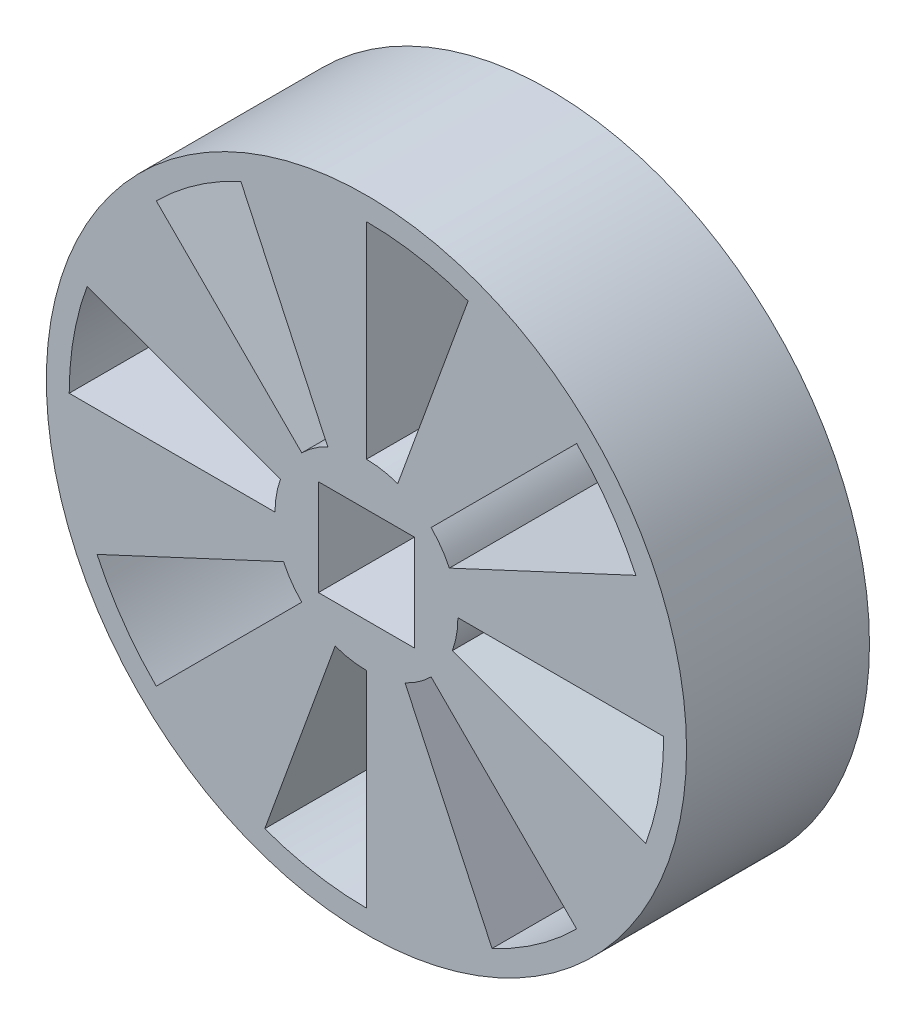
SolidWorks part; units mm, degrees
ref_plane "Спереди" through (0, 0, 0) normal (0, 0, 1) x (1, 0, 0)
ref_plane "Сверху" through (0, 0, 0) normal (0, 1, 0) x (1, 0, 0)
ref_plane "Справа" through (0, 0, 0) normal (1, 0, 0) x (0, 0, -1)
sketch "Эскиз2" plane through (0, 0, 0) normal (0, 0, 1) x (1, 0, 0)
  line L0 (0, 10) -> (0, 32.5)
  line L1 (-5.25, -5.25) -> (5.25, -5.25)
  line L2 (-5.25, -5.25) -> (-5.25, 5.25)
  line L3 (-5.25, 5.25) -> (5.25, 5.25)
  line L4 (5.25, -5.25) -> (5.25, 5.25)
  line L5 (-5.25, -5.25) -> (5.25, 5.25) construction
  line L6 (-5.25, 5.25) -> (5.25, -5.25) construction
  line L7 (3.4202, 9.3969) -> (11.1157, 30.54)
  line L8 (7.0711, 7.0711) -> (22.981, 22.981)
  line L9 (9.0631, 4.2262) -> (29.455, 13.7351)
  line L10 (10, 0) -> (32.5, 0)
  line L11 (9.3969, -3.4202) -> (30.54, -11.1157)
  line L12 (7.0711, -7.0711) -> (22.981, -22.981)
  line L13 (4.2262, -9.0631) -> (13.7351, -29.455)
  line L14 (0, -10) -> (0, -32.5)
  line L15 (-3.4202, -9.3969) -> (-11.1157, -30.54)
  line L16 (-7.0711, -7.0711) -> (-22.981, -22.981)
  line L17 (-9.0631, -4.2262) -> (-29.455, -13.7351)
  line L18 (-10, 0) -> (-32.5, 0)
  line L19 (-9.3969, 3.4202) -> (-30.54, 11.1157)
  line L20 (-7.0711, 7.0711) -> (-22.981, 22.981)
  line L21 (-4.2262, 9.0631) -> (-13.7351, 29.455)
  circle A0 centre (0, 0) radius 35
  arc A1 (-4.2262, 9.0631) -> (-7.0711, 7.0711) centre (0, 0) ccw
  arc A2 (-13.7351, 29.455) -> (-22.981, 22.981) centre (0, 0) ccw
  arc A3 (0, 10) -> (3.4202, 9.3969) centre (0, 0) cw
  arc A4 (0, 32.5) -> (11.1157, 30.54) centre (0, 0) cw
  arc A5 (11.1157, 30.54) -> (0, 32.5) centre (0, 0) ccw
  arc A6 (29.455, 13.7351) -> (22.981, 22.981) centre (0, 0) ccw
  arc A7 (9.0631, 4.2262) -> (7.0711, 7.0711) centre (0, 0) ccw
  arc A8 (9.3969, -3.4202) -> (10, 0) centre (0, 0) ccw
  arc A9 (30.54, -11.1157) -> (32.5, 0) centre (0, 0) ccw
  arc A10 (13.7351, -29.455) -> (22.981, -22.981) centre (0, 0) ccw
  arc A11 (4.2262, -9.0631) -> (7.0711, -7.0711) centre (0, 0) ccw
  arc A12 (-3.4202, -9.3969) -> (0, -10) centre (0, 0) ccw
  arc A13 (-11.1157, -30.54) -> (0, -32.5) centre (0, 0) ccw
  arc A14 (-29.455, -13.7351) -> (-22.981, -22.981) centre (0, 0) ccw
  arc A15 (-9.0631, -4.2262) -> (-7.0711, -7.0711) centre (0, 0) ccw
  arc A16 (-9.3969, 3.4202) -> (-10, 0) centre (0, 0) ccw
  arc A17 (-30.54, 11.1157) -> (-32.5, 0) centre (0, 0) ccw
  point P43 (0, 0)
  dimension "D1" = 70
  dimension "D2" = 20
  dimension "D5" = 65
  dimension "D3" = 10.5
  dimension "D4" = 10.5
  dimension "D6" = 8
extrude "Бобышка-Вытянуть1" add sketch "Эскиз2" along normal blind 20 contours A0 A17 L19 A16 L18 A13 L15 A12 L14 A9 L11 A8 L10 A2 L21 A1 L20 L4 L1 L2 L3 L0 A4 L7 A3 L9 A7 L8 A6 L13 A11 L12 A10 L17 A15 L16 A14
